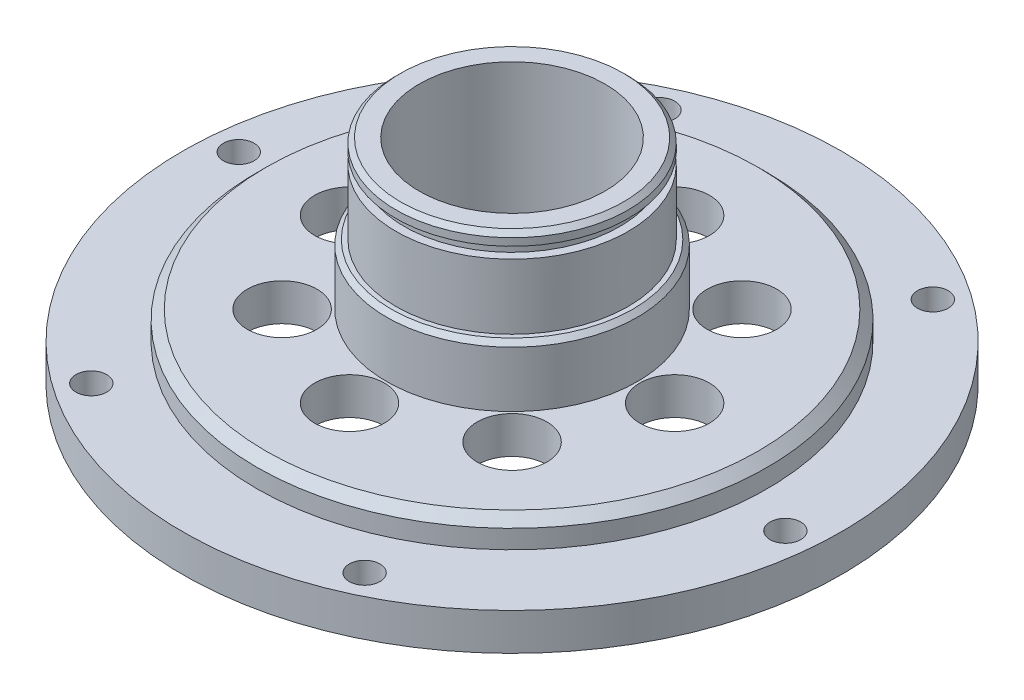
SolidWorks part; units mm, degrees
material "6061 合金"
ref_plane "前视基准面" through (0, 0, 0) normal (0, 0, 1) x (1, 0, 0)
ref_plane "上视基准面" through (0, 0, 0) normal (0, 1, 0) x (1, 0, 0)
ref_plane "右视基准面" through (0, 0, 0) normal (1, 0, 0) x (0, 0, -1)
other "Configuration Table"
sketch "草图1" plane through (0, 0, 0) normal (0, 0, 1) x (1, 0, 0)
  line L0 (-35.475, 0) -> (-23.475, 0)
  line L1 (-23.475, 0) -> (-23.475, 3)
  line L2 (-23.475, 3) -> (-10, 3)
  line L3 (-10, 3) -> (-10, 23)
  line L4 (-10, 23) -> (-12.5, 23)
  line L5 (-12.5, 23) -> (-12.5, 7)
  line L6 (-12.5, 7) -> (-27.475, 7)
  line L7 (-27.475, 7) -> (-27.475, 4)
  line L8 (-27.475, 4) -> (-35.475, 4)
  line L9 (-35.475, 4) -> (-35.475, 0)
  line L10 (0, 0) -> (0, 41.1545) construction
  dimension "D1" = 4
  dimension "D2" = 54.95
  dimension "D3" = 3
  dimension "D4" = 8
  dimension "D5" = 4
  dimension "D6" = 4
  dimension "D7" = 20
  dimension "D8" = 25
  dimension "D9" = 16
revolve "旋转1" add sketch "草图1" angle 360 about L10
sketch "草图2" plane through (0, 7, 0) normal (0, 1, 0) x (1, 0, 0)
  circle A0 centre (0, 0) radius 17.5 construction
  circle A1 centre (0, 17.5) radius 3.75
  circle A2 centre (12.3744, 12.3744) radius 3.75
  circle A3 centre (17.5, 0) radius 3.75
  circle A4 centre (12.3744, -12.3744) radius 3.75
  circle A5 centre (0, -17.5) radius 3.75
  circle A6 centre (-12.3744, -12.3744) radius 3.75
  circle A7 centre (-17.5, 0) radius 3.75
  circle A8 centre (-12.3744, 12.3744) radius 3.75
  point P21 (0, 0)
  dimension "D1" = 35
  dimension "D2" = 7.5
  dimension "D3" = 8
extrude "切除-拉伸1" cut sketch "草图2" against normal blind 10
chamfer "倒角1" distance 1 angle 45 1 edges at (0, 0, -23.475)
chamfer "倒角2" distance 1 angle 45 1 edges at (0, 7, -27.475)
sketch "草图3" plane through (0, 0, 0) normal (0, 0, 1) x (1, 0, 0)
  line L0 (0, 0) -> (0, 25.3719) construction
  line L1 (12.5, 21.7) -> (11.6, 21.7)
  line L2 (12.5, 7) -> (12.5, 23) construction
  line L3 (11.6, 21.7) -> (11.6, 20.5)
  line L4 (11.6, 20.5) -> (12.5, 20.5)
  line L5 (12.5, 20.5) -> (12.5, 21.7)
  line L6 (12.5, 23) -> (-12.5, 23) construction
  dimension "D1" = 23.2
  dimension "D2" = 1.3
  dimension "D3" = 1.2
revolve "切除-旋转1" cut sketch "草图3" angle 360 about L0
chamfer "倒角3" distance 0.5 angle 45 1 edges at (0, 23, -12.5)
sketch "草图4" plane through (0, 4, 0) normal (0, 1, 0) x (1, 0, 0)
  circle A0 centre (18.7348, 26.5567) radius 2 construction
  circle A1 centre (18.7348, 26.5567) radius 2 construction
  circle A2 centre (0, 0) radius 32.5 construction
hole_wizard "M4 螺纹孔1" positions "草图5" profile "草图6" tap size "M4" standard "GB" end condition through all
sketch "草图5" plane through (0, 4, 0) normal (0, 1, 0) x (1, 0, 0)
  point P0 (18.7348, 26.5567)
sketch "草图6" plane through (18.7348, 4, -26.5567) normal (1, 0, 0) x (0, 0, 1)
  line L0 (0, 0) -> (0, 4)
  line L1 (0, 4) -> (1.65, 4)
  line L2 (1.65, 4) -> (1.65, 0)
  line L5 (1.65, 0) -> (0, 0)
  line L11 (0, -6.35) -> (0, 107.95) construction
  dimension "通孔螺纹孔钻头直径" = 3.3
  dimension "通孔螺纹孔钻头深度" = 4
cosmetic thread "孔螺蚊线1" parameters "D2"=4
pattern_circular "阵列(圆周)1" count 6 over 360 about axis through (0, 0, 0) along (0, 1, 0) of "M4 螺纹孔1"
sketch "草图7" plane through (0, 7, 0) normal (0, 1, 0) x (1, 0, 0)
  circle A0 centre (0, 0) radius 13.5
  circle A1 centre (0, 0) radius 12.5 construction
  circle A2 centre (0, 0) radius 12.5 construction
  circle A3 centre (0, 0) radius 12.5
  dimension "D1" = 1
extrude "凸台-拉伸1" add sketch "草图7" along normal blind 6.5
chamfer "倒角4" distance 0.5 angle 45 1 edges at (0, 13.5, 13.5)
